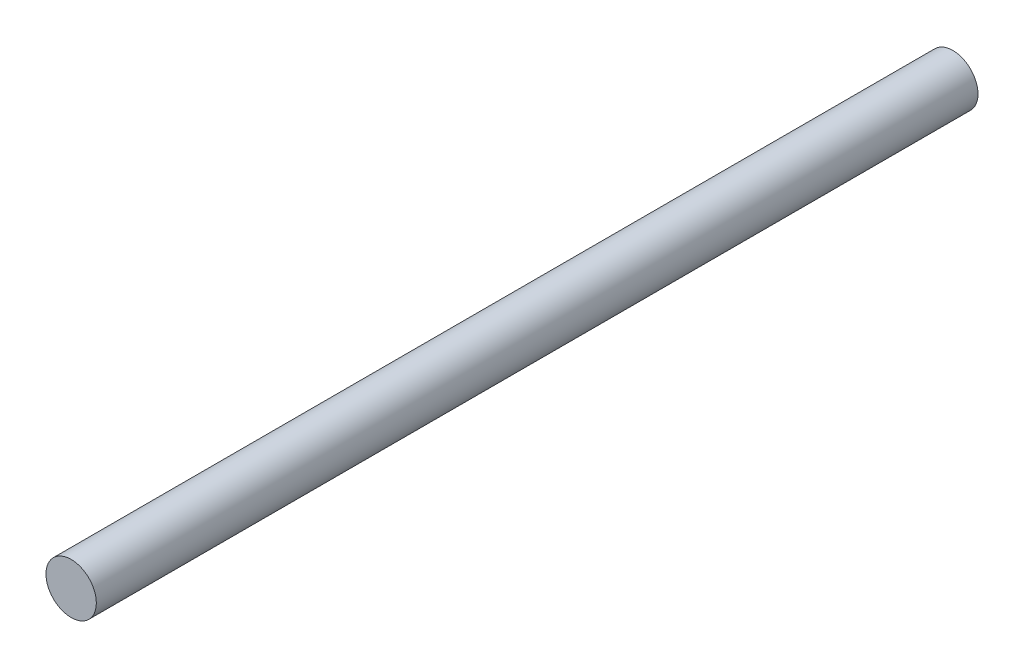
SolidWorks part; units mm, degrees
ref_plane "前视基准面" through (0, 0, 0) normal (0, 0, 1) x (1, 0, 0)
ref_plane "上视基准面" through (0, 0, 0) normal (0, 1, 0) x (1, 0, 0)
ref_plane "右视基准面" through (0, 0, 0) normal (1, 0, 0) x (0, 0, -1)
sketch "草图1" plane through (0, 0, 0) normal (0, 0, 1) x (1, 0, 0)
  circle A0 centre (0, 0) radius 10
  dimension "D1" = 20
extrude "凸台-拉伸1" add sketch "草图1" along normal blind 350
